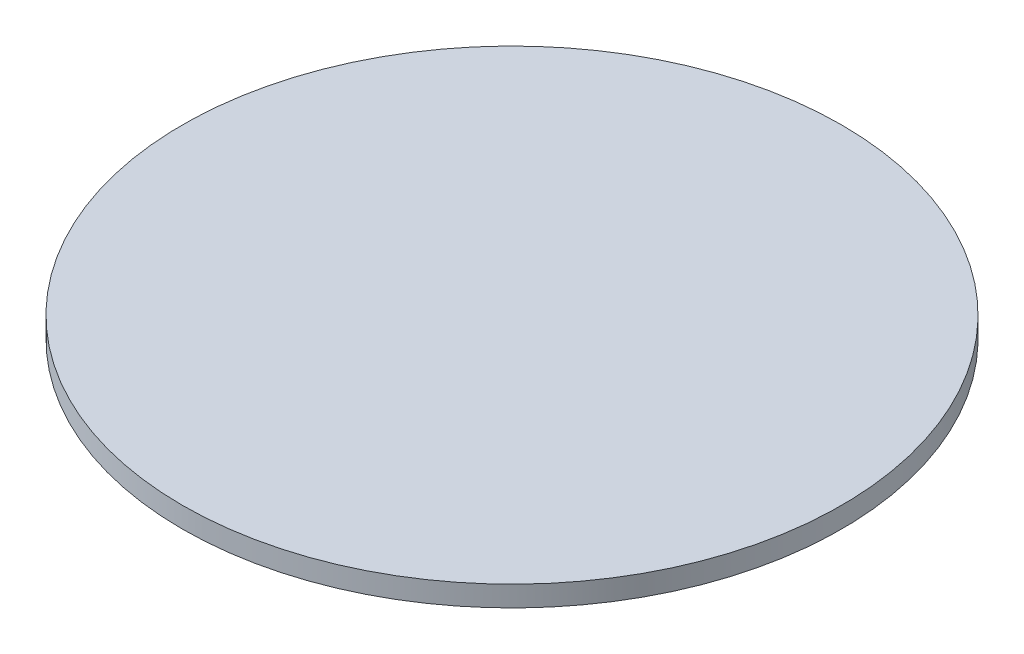
SolidWorks part; units mm, degrees
ref_plane "Front Plane" through (0, 0, 0) normal (0, 0, 1) x (1, 0, 0)
ref_plane "Top Plane" through (0, 0, 0) normal (0, 1, 0) x (1, 0, 0)
ref_plane "Right Plane" through (0, 0, 0) normal (1, 0, 0) x (0, 0, -1)
sketch "Sketch1" plane through (0, 0, 0) normal (0, 1, 0) x (1, 0, 0)
  circle A0 centre (0, 0) radius 25.4
extrude "Boss-Extrude1" add sketch "Sketch1" along normal blind 1.5875
